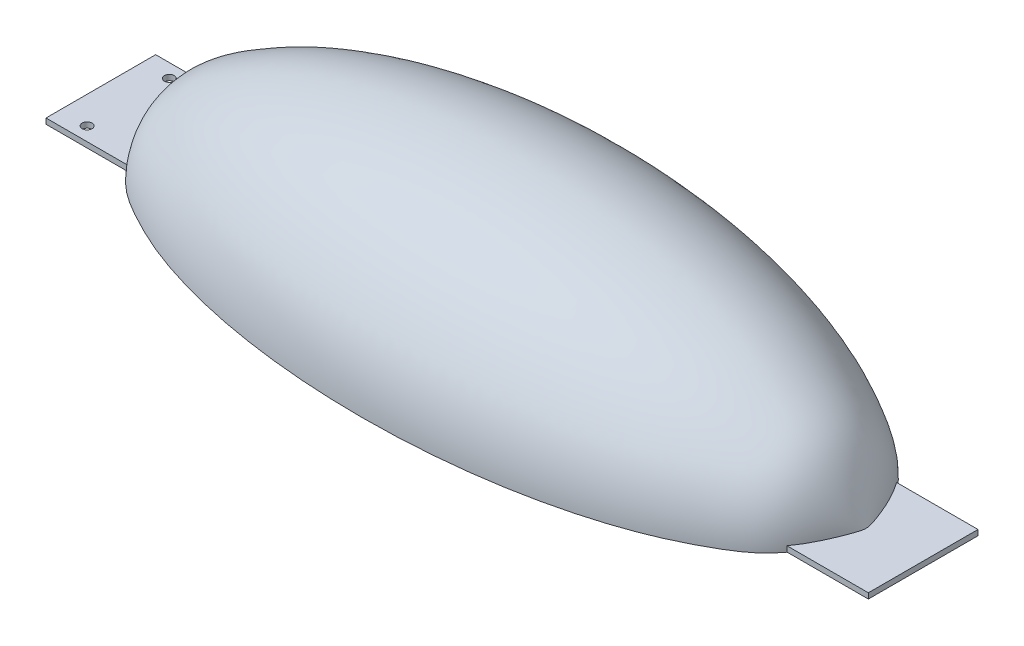
SolidWorks part; units mm, degrees
ref_plane "Front Plane" through (0, 0, 0) normal (0, 0, 1) x (1, 0, 0)
ref_plane "Top Plane" through (0, 0, 0) normal (0, 1, 0) x (1, 0, 0)
ref_plane "Right Plane" through (0, 0, 0) normal (1, 0, 0) x (0, 0, -1)
sketch "Sketch1" plane through (0, 0, 0) normal (0, 0, 1) x (1, 0, 0)
  line L0 (-260, 0) -> (0, 0)
  line L1 (10, 0) -> (-270, 0) construction
  spline S0 degree 3 poles (0, 0) (-3.3473, 8.8305) (-8.6371, 22.7855) (-25.561, 33.0216) (-38.6922, 39.4342) (-51.8523, 44.1238) (-64.8995, 47.7494) (-77.9366, 50.515) (-90.9583, 52.5666) (-103.9749, 53.9839) (-116.9881, 54.8167) (-130, 55.0915) (-143.0119, 54.8167) (-156.0251, 53.9839) (-169.0417, 52.5666) (-182.0634, 50.515) (-195.1005, 47.7494) (-208.1477, 44.1238) (-221.3078, 39.4342) (-234.439, 33.0216) (-251.3629, 22.7855) (-256.6527, 8.8305) (-260, 0) knots 0 0 0 0 0.090649 0.143253 0.191239 0.237212 0.282077 0.326262 0.370011 0.41348 0.45678 0.5 0.54322 0.58652 0.629989 0.673738 0.717923 0.762788 0.808761 0.856747 0.909351 1 1 1 1
revolve "Revolve1" add sketch "Sketch1" angle 360 about L1
sketch "Sketch2" plane through (0, 0, 0) normal (0, 1, 0) x (1, 0, 0)
  line L0 (-310, 80) -> (50, 80)
  line L1 (50, 80) -> (50, -80)
  line L2 (50, -80) -> (-310, -80)
  line L3 (-310, -80) -> (-310, 80)
extrude "Cut-Extrude1" cut sketch "Sketch2" against normal blind 80
sketch "Sketch3" plane through (0, 0, 0) normal (0, 1, 0) x (1, 0, 0)
  line L0 (-280, 20) -> (-250, 20)
  line L1 (-250, 20) -> (-250, -20)
  line L2 (-250, -20) -> (-280, -20)
  line L3 (-280, -20) -> (-280, 20)
  line L4 (-10, 20) -> (20, 20)
  line L5 (20, 20) -> (20, -20)
  line L6 (20, -20) -> (-10, -20)
  line L7 (-10, -20) -> (-10, 20)
extrude "Boss-Extrude1" add sketch "Sketch3" along normal blind 2
sketch "Sketch4" plane through (0, 0, 0) normal (0, 1, 0) x (1, 0, 0)
  circle A0 centre (-270, -15) radius 1.8
  circle A1 centre (-270, 15) radius 1.8
extrude "Cut-Extrude2" cut sketch "Sketch4" along normal blind 3
